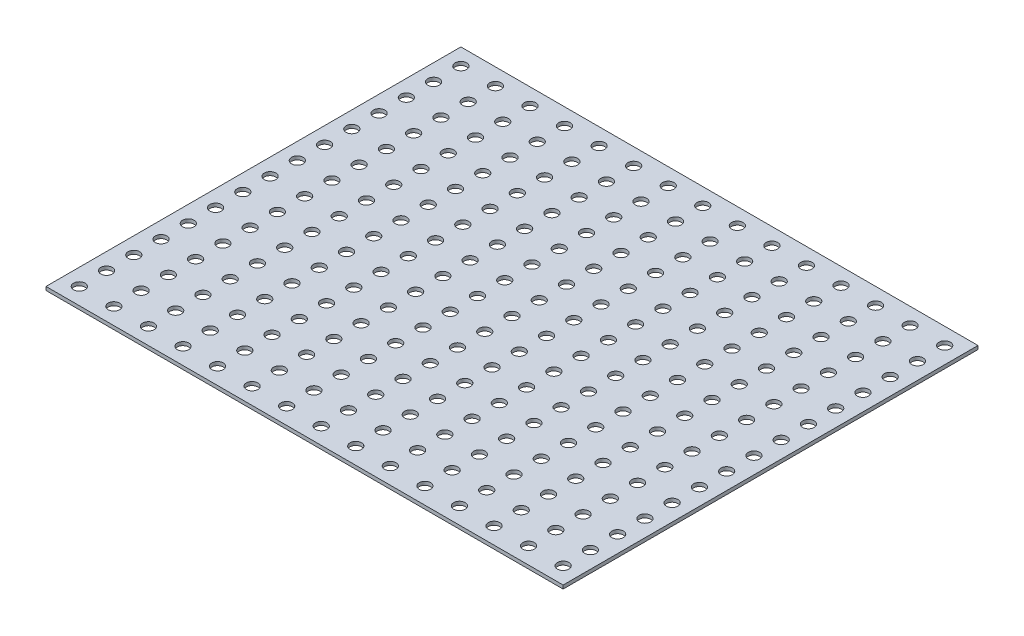
SolidWorks part; units mm, degrees
ref_plane "Front Plane" through (0, 0, 0) normal (0, 0, 1) x (1, 0, 0)
ref_plane "Top Plane" through (0, 0, 0) normal (0, 1, 0) x (1, 0, 0)
ref_plane "Right Plane" through (0, 0, 0) normal (1, 0, 0) x (0, 0, -1)
sketch "Sketch1" plane through (0, 0, 0) normal (0, 1, 0) x (1, 0, 0)
  line L0 (-18.1912, 12.0288) -> (-5.5112, 12.0288) construction
  line L1 (-18.1912, 12.0288) -> (-18.1912, 18.1388) construction
  line L2 (-18.1912, 12.0288) -> (-24.3012, 12.0288) construction
  line L3 (-24.3012, 12.0288) -> (-24.3012, 18.1388) construction
  line L4 (-24.3012, 18.1388) -> (-18.1912, 18.1388) construction
  line L5 (159.3288, -127.9712) -> (159.3288, -134.0812) construction
  line L6 (159.3288, -134.0812) -> (165.4388, -134.0812) construction
  line L8 (165.4388, -134.0812) -> (-24.3012, -134.0812)
  line L9 (165.4388, -134.0812) -> (165.4388, 18.1388)
  line L10 (165.4388, 18.1388) -> (-24.3012, 18.1388)
  line L11 (-24.3012, -134.0812) -> (-24.3012, 18.1388)
  circle A0 centre (-18.1912, 12.0288) radius 2.11
  circle A1 centre (-5.5112, 12.0288) radius 2.11
  circle A2 centre (7.1688, 12.0288) radius 2.11
  circle A3 centre (19.8488, 12.0288) radius 2.11
  circle A4 centre (32.5288, 12.0288) radius 2.11
  circle A5 centre (45.2088, 12.0288) radius 2.11
  circle A6 centre (57.8888, 12.0288) radius 2.11
  circle A7 centre (70.5688, 12.0288) radius 2.11
  circle A8 centre (83.2488, 12.0288) radius 2.11
  circle A9 centre (95.9288, 12.0288) radius 2.11
  circle A10 centre (108.6088, 12.0288) radius 2.11
  circle A11 centre (121.2888, 12.0288) radius 2.11
  circle A12 centre (133.9688, 12.0288) radius 2.11
  circle A13 centre (146.6488, 12.0288) radius 2.11
  circle A14 centre (159.3288, 12.0288) radius 2.11
  circle A15 centre (-5.5112, 2.0288) radius 2.11
  circle A16 centre (7.1688, 2.0288) radius 2.11
  circle A17 centre (19.8488, 2.0288) radius 2.11
  circle A18 centre (32.5288, 2.0288) radius 2.11
  circle A19 centre (45.2088, 2.0288) radius 2.11
  circle A20 centre (57.8888, 2.0288) radius 2.11
  circle A21 centre (70.5688, 2.0288) radius 2.11
  circle A22 centre (83.2488, 2.0288) radius 2.11
  circle A23 centre (95.9288, 2.0288) radius 2.11
  circle A24 centre (108.6088, 2.0288) radius 2.11
  circle A25 centre (121.2888, 2.0288) radius 2.11
  circle A26 centre (133.9688, 2.0288) radius 2.11
  circle A27 centre (146.6488, 2.0288) radius 2.11
  circle A28 centre (159.3288, 2.0288) radius 2.11
  circle A29 centre (-5.5112, -7.9712) radius 2.11
  circle A30 centre (7.1688, -7.9712) radius 2.11
  circle A31 centre (19.8488, -7.9712) radius 2.11
  circle A32 centre (32.5288, -7.9712) radius 2.11
  circle A33 centre (45.2088, -7.9712) radius 2.11
  circle A34 centre (57.8888, -7.9712) radius 2.11
  circle A35 centre (70.5688, -7.9712) radius 2.11
  circle A36 centre (83.2488, -7.9712) radius 2.11
  circle A37 centre (95.9288, -7.9712) radius 2.11
  circle A38 centre (108.6088, -7.9712) radius 2.11
  circle A39 centre (121.2888, -7.9712) radius 2.11
  circle A40 centre (133.9688, -7.9712) radius 2.11
  circle A41 centre (146.6488, -7.9712) radius 2.11
  circle A42 centre (159.3288, -7.9712) radius 2.11
  circle A43 centre (-5.5112, -17.9712) radius 2.11
  circle A44 centre (7.1688, -17.9712) radius 2.11
  circle A45 centre (19.8488, -17.9712) radius 2.11
  circle A46 centre (32.5288, -17.9712) radius 2.11
  circle A47 centre (45.2088, -17.9712) radius 2.11
  circle A48 centre (57.8888, -17.9712) radius 2.11
  circle A49 centre (70.5688, -17.9712) radius 2.11
  circle A50 centre (83.2488, -17.9712) radius 2.11
  circle A51 centre (95.9288, -17.9712) radius 2.11
  circle A52 centre (108.6088, -17.9712) radius 2.11
  circle A53 centre (121.2888, -17.9712) radius 2.11
  circle A54 centre (133.9688, -17.9712) radius 2.11
  circle A55 centre (146.6488, -17.9712) radius 2.11
  circle A56 centre (159.3288, -17.9712) radius 2.11
  circle A57 centre (-5.5112, -27.9712) radius 2.11
  circle A58 centre (7.1688, -27.9712) radius 2.11
  circle A59 centre (19.8488, -27.9712) radius 2.11
  circle A60 centre (32.5288, -27.9712) radius 2.11
  circle A61 centre (45.2088, -27.9712) radius 2.11
  circle A62 centre (57.8888, -27.9712) radius 2.11
  circle A63 centre (70.5688, -27.9712) radius 2.11
  circle A64 centre (83.2488, -27.9712) radius 2.11
  circle A65 centre (95.9288, -27.9712) radius 2.11
  circle A66 centre (108.6088, -27.9712) radius 2.11
  circle A67 centre (121.2888, -27.9712) radius 2.11
  circle A68 centre (133.9688, -27.9712) radius 2.11
  circle A69 centre (146.6488, -27.9712) radius 2.11
  circle A70 centre (159.3288, -27.9712) radius 2.11
  circle A71 centre (-5.5112, -37.9712) radius 2.11
  circle A72 centre (7.1688, -37.9712) radius 2.11
  circle A73 centre (19.8488, -37.9712) radius 2.11
  circle A74 centre (32.5288, -37.9712) radius 2.11
  circle A75 centre (45.2088, -37.9712) radius 2.11
  circle A76 centre (57.8888, -37.9712) radius 2.11
  circle A77 centre (70.5688, -37.9712) radius 2.11
  circle A78 centre (83.2488, -37.9712) radius 2.11
  circle A79 centre (95.9288, -37.9712) radius 2.11
  circle A80 centre (108.6088, -37.9712) radius 2.11
  circle A81 centre (121.2888, -37.9712) radius 2.11
  circle A82 centre (133.9688, -37.9712) radius 2.11
  circle A83 centre (146.6488, -37.9712) radius 2.11
  circle A84 centre (159.3288, -37.9712) radius 2.11
  circle A85 centre (-5.5112, -47.9712) radius 2.11
  circle A86 centre (7.1688, -47.9712) radius 2.11
  circle A87 centre (19.8488, -47.9712) radius 2.11
  circle A88 centre (32.5288, -47.9712) radius 2.11
  circle A89 centre (45.2088, -47.9712) radius 2.11
  circle A90 centre (57.8888, -47.9712) radius 2.11
  circle A91 centre (70.5688, -47.9712) radius 2.11
  circle A92 centre (83.2488, -47.9712) radius 2.11
  circle A93 centre (95.9288, -47.9712) radius 2.11
  circle A94 centre (108.6088, -47.9712) radius 2.11
  circle A95 centre (121.2888, -47.9712) radius 2.11
  circle A96 centre (133.9688, -47.9712) radius 2.11
  circle A97 centre (146.6488, -47.9712) radius 2.11
  circle A98 centre (159.3288, -47.9712) radius 2.11
  circle A99 centre (-5.5112, -57.9712) radius 2.11
  circle A100 centre (7.1688, -57.9712) radius 2.11
  circle A101 centre (19.8488, -57.9712) radius 2.11
  circle A102 centre (32.5288, -57.9712) radius 2.11
  circle A103 centre (45.2088, -57.9712) radius 2.11
  circle A104 centre (57.8888, -57.9712) radius 2.11
  circle A105 centre (70.5688, -57.9712) radius 2.11
  circle A106 centre (83.2488, -57.9712) radius 2.11
  circle A107 centre (95.9288, -57.9712) radius 2.11
  circle A108 centre (108.6088, -57.9712) radius 2.11
  circle A109 centre (121.2888, -57.9712) radius 2.11
  circle A110 centre (133.9688, -57.9712) radius 2.11
  circle A111 centre (146.6488, -57.9712) radius 2.11
  circle A112 centre (159.3288, -57.9712) radius 2.11
  circle A113 centre (-5.5112, -67.9712) radius 2.11
  circle A114 centre (7.1688, -67.9712) radius 2.11
  circle A115 centre (19.8488, -67.9712) radius 2.11
  circle A116 centre (32.5288, -67.9712) radius 2.11
  circle A117 centre (45.2088, -67.9712) radius 2.11
  circle A118 centre (57.8888, -67.9712) radius 2.11
  circle A119 centre (70.5688, -67.9712) radius 2.11
  circle A120 centre (83.2488, -67.9712) radius 2.11
  circle A121 centre (95.9288, -67.9712) radius 2.11
  circle A122 centre (108.6088, -67.9712) radius 2.11
  circle A123 centre (121.2888, -67.9712) radius 2.11
  circle A124 centre (133.9688, -67.9712) radius 2.11
  circle A125 centre (146.6488, -67.9712) radius 2.11
  circle A126 centre (159.3288, -67.9712) radius 2.11
  circle A127 centre (-5.5112, -77.9712) radius 2.11
  circle A128 centre (7.1688, -77.9712) radius 2.11
  circle A129 centre (19.8488, -77.9712) radius 2.11
  circle A130 centre (32.5288, -77.9712) radius 2.11
  circle A131 centre (45.2088, -77.9712) radius 2.11
  circle A132 centre (57.8888, -77.9712) radius 2.11
  circle A133 centre (70.5688, -77.9712) radius 2.11
  circle A134 centre (83.2488, -77.9712) radius 2.11
  circle A135 centre (95.9288, -77.9712) radius 2.11
  circle A136 centre (108.6088, -77.9712) radius 2.11
  circle A137 centre (121.2888, -77.9712) radius 2.11
  circle A138 centre (133.9688, -77.9712) radius 2.11
  circle A139 centre (146.6488, -77.9712) radius 2.11
  circle A140 centre (159.3288, -77.9712) radius 2.11
  circle A141 centre (-5.5112, -87.9712) radius 2.11
  circle A142 centre (7.1688, -87.9712) radius 2.11
  circle A143 centre (19.8488, -87.9712) radius 2.11
  circle A144 centre (32.5288, -87.9712) radius 2.11
  circle A145 centre (45.2088, -87.9712) radius 2.11
  circle A146 centre (57.8888, -87.9712) radius 2.11
  circle A147 centre (70.5688, -87.9712) radius 2.11
  circle A148 centre (83.2488, -87.9712) radius 2.11
  circle A149 centre (95.9288, -87.9712) radius 2.11
  circle A150 centre (108.6088, -87.9712) radius 2.11
  circle A151 centre (121.2888, -87.9712) radius 2.11
  circle A152 centre (133.9688, -87.9712) radius 2.11
  circle A153 centre (146.6488, -87.9712) radius 2.11
  circle A154 centre (159.3288, -87.9712) radius 2.11
  circle A155 centre (-5.5112, -97.9712) radius 2.11
  circle A156 centre (7.1688, -97.9712) radius 2.11
  circle A157 centre (19.8488, -97.9712) radius 2.11
  circle A158 centre (32.5288, -97.9712) radius 2.11
  circle A159 centre (45.2088, -97.9712) radius 2.11
  circle A160 centre (57.8888, -97.9712) radius 2.11
  circle A161 centre (70.5688, -97.9712) radius 2.11
  circle A162 centre (83.2488, -97.9712) radius 2.11
  circle A163 centre (95.9288, -97.9712) radius 2.11
  circle A164 centre (108.6088, -97.9712) radius 2.11
  circle A165 centre (121.2888, -97.9712) radius 2.11
  circle A166 centre (133.9688, -97.9712) radius 2.11
  circle A167 centre (146.6488, -97.9712) radius 2.11
  circle A168 centre (159.3288, -97.9712) radius 2.11
  circle A169 centre (-5.5112, -107.9712) radius 2.11
  circle A170 centre (7.1688, -107.9712) radius 2.11
  circle A171 centre (19.8488, -107.9712) radius 2.11
  circle A172 centre (32.5288, -107.9712) radius 2.11
  circle A173 centre (45.2088, -107.9712) radius 2.11
  circle A174 centre (57.8888, -107.9712) radius 2.11
  circle A175 centre (70.5688, -107.9712) radius 2.11
  circle A176 centre (83.2488, -107.9712) radius 2.11
  circle A177 centre (95.9288, -107.9712) radius 2.11
  circle A178 centre (108.6088, -107.9712) radius 2.11
  circle A179 centre (121.2888, -107.9712) radius 2.11
  circle A180 centre (133.9688, -107.9712) radius 2.11
  circle A181 centre (146.6488, -107.9712) radius 2.11
  circle A182 centre (159.3288, -107.9712) radius 2.11
  circle A183 centre (-5.5112, -117.9712) radius 2.11
  circle A184 centre (7.1688, -117.9712) radius 2.11
  circle A185 centre (19.8488, -117.9712) radius 2.11
  circle A186 centre (32.5288, -117.9712) radius 2.11
  circle A187 centre (45.2088, -117.9712) radius 2.11
  circle A188 centre (57.8888, -117.9712) radius 2.11
  circle A189 centre (70.5688, -117.9712) radius 2.11
  circle A190 centre (83.2488, -117.9712) radius 2.11
  circle A191 centre (95.9288, -117.9712) radius 2.11
  circle A192 centre (108.6088, -117.9712) radius 2.11
  circle A193 centre (121.2888, -117.9712) radius 2.11
  circle A194 centre (133.9688, -117.9712) radius 2.11
  circle A195 centre (146.6488, -117.9712) radius 2.11
  circle A196 centre (159.3288, -117.9712) radius 2.11
  circle A197 centre (-5.5112, -127.9712) radius 2.11
  circle A198 centre (7.1688, -127.9712) radius 2.11
  circle A199 centre (19.8488, -127.9712) radius 2.11
  circle A200 centre (32.5288, -127.9712) radius 2.11
  circle A201 centre (45.2088, -127.9712) radius 2.11
  circle A202 centre (57.8888, -127.9712) radius 2.11
  circle A203 centre (70.5688, -127.9712) radius 2.11
  circle A204 centre (83.2488, -127.9712) radius 2.11
  circle A205 centre (95.9288, -127.9712) radius 2.11
  circle A206 centre (108.6088, -127.9712) radius 2.11
  circle A207 centre (121.2888, -127.9712) radius 2.11
  circle A208 centre (133.9688, -127.9712) radius 2.11
  circle A209 centre (146.6488, -127.9712) radius 2.11
  circle A210 centre (159.3288, -127.9712) radius 2.11
  circle A211 centre (-18.1912, 2.0288) radius 2.11
  circle A212 centre (-18.1912, -7.9712) radius 2.11
  circle A213 centre (-18.1912, -17.9712) radius 2.11
  circle A214 centre (-18.1912, -27.9712) radius 2.11
  circle A215 centre (-18.1912, -37.9712) radius 2.11
  circle A216 centre (-18.1912, -47.9712) radius 2.11
  circle A217 centre (-18.1912, -57.9712) radius 2.11
  circle A218 centre (-18.1912, -67.9712) radius 2.11
  circle A219 centre (-18.1912, -77.9712) radius 2.11
  circle A220 centre (-18.1912, -87.9712) radius 2.11
  circle A221 centre (-18.1912, -97.9712) radius 2.11
  circle A222 centre (-18.1912, -107.9712) radius 2.11
  circle A223 centre (-18.1912, -117.9712) radius 2.11
  circle A224 centre (-18.1912, -127.9712) radius 2.11
  dimension "D1" = 4.22
  dimension "D2" = 15
  dimension "D4" = 12.68
  dimension "D5" = 6.11
  dimension "D6" = 6.11
  dimension "D7" = 6.11
  dimension "D8" = 6.11
  dimension "D3" = 15
extrude "Boss-Extrude1" add sketch "Sketch1" against normal blind 1.3
sketch "Sketch4" plane through (165.4388, 0, 0) normal (1, 0, 0) x (0, 0, -1)
  line L0 (-134.0812, 0) -> (-134.0812, -14.22) construction
  line L1 (83.721, 0) -> (-83.721, 0) construction
  line L2 (-134.0812, -1.3) -> (-134.0812, 0) construction
  line L3 (-134.0812, -14.22) -> (18.1388, -14.22) construction
  line L4 (18.1388, -14.22) -> (18.1388, 0) construction
  line L5 (18.1388, -1.3) -> (18.1388, 0) construction
  line L6 (18.1388, -1.3) -> (18.1388, -14.22) construction
  line L7 (18.1388, -7.76) -> (-134.0812, -7.76) construction
  line L8 (-127.8612, -4.4108) -> (-127.8612, -11.1092) construction
  line L9 (-125.7512, -4.4108) -> (-125.7512, -11.1092)
  line L10 (-129.9712, -4.4108) -> (-129.9712, -11.1092)
  arc A0 (-125.7512, -4.4108) -> (-129.9712, -4.4108) centre (-127.8612, -4.4108) ccw
  arc A1 (-129.9712, -11.1092) -> (-125.7512, -11.1092) centre (-127.8612, -11.1092) ccw
  point P11 (18.1388, -7.76)
  point P17 (-127.8612, -7.76)
  point P22 (-127.8612, -7.76)
  dimension "D1" = 14.22
  dimension "D2" = 6.22
  dimension "D3" = 4.22
